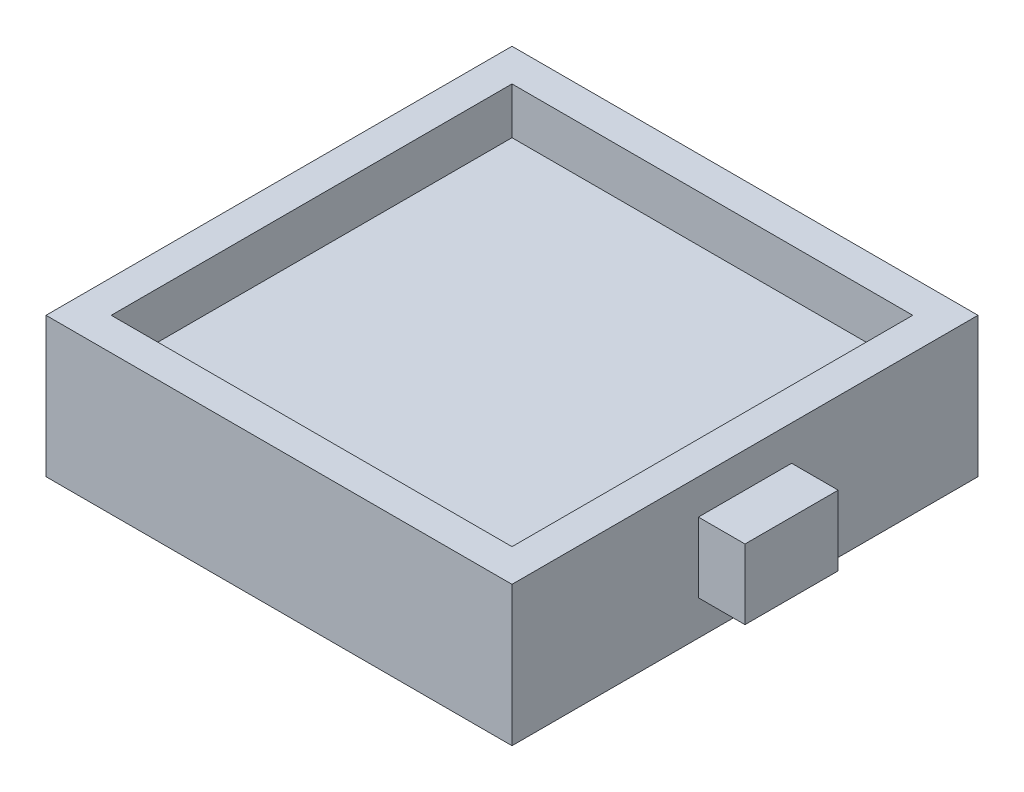
SolidWorks part; units mm, degrees
material "AISI 1020"
ref_plane "Front Plane" through (0, 0, 0) normal (0, 0, 1) x (1, 0, 0)
ref_plane "Top Plane" through (0, 0, 0) normal (0, 1, 0) x (1, 0, 0)
ref_plane "Right Plane" through (0, 0, 0) normal (1, 0, 0) x (0, 0, -1)
sketch "Sketch1" plane through (0, 0, 0) normal (0, 1, 0) x (1, 0, 0)
  line L1 (-50, 50) -> (50, 50)
  line L2 (-50, 50) -> (-50, -50)
  line L3 (-50, -50) -> (50, -50)
  line L4 (50, 50) -> (50, -50)
  line L5 (-50, 50) -> (50, -50) construction
  line L6 (-50, -50) -> (50, 50) construction
  point P0 (0, 0)
  dimension "D1" = 100
  dimension "D2" = 100
extrude "Boss-Extrude1" add sketch "Sketch1" against normal blind 30
sketch "Sketch2" plane through (0, 0, 0) normal (0, 1, 0) x (1, 0, 0)
  line L0 (50, 50) -> (-50, 50) construction
  line L1 (-43, -43) -> (43, -43)
  line L2 (-43, -43) -> (-43, 43)
  line L3 (-43, 43) -> (43, 43)
  line L4 (43, -43) -> (43, 43)
  line L5 (-43, -43) -> (43, 43) construction
  line L6 (-43, 43) -> (43, -43) construction
  line L7 (-50, 50) -> (-50, -50) construction
  point P0 (0, 0)
  dimension "D1" = 7
  dimension "D2" = 7
extrude "Cut-Extrude1" cut sketch "Sketch2" against normal blind 10
sketch "Sketch3" plane through (50, 0, 0) normal (1, 0, 0) x (0, 0, -1)
  line L0 (0, 0) -> (0, -15) construction
  line L1 (-10, -22.5) -> (10, -22.5)
  line L2 (-10, -22.5) -> (-10, -7.5)
  line L3 (-10, -7.5) -> (10, -7.5)
  line L4 (10, -22.5) -> (10, -7.5)
  line L5 (-10, -22.5) -> (10, -7.5) construction
  line L6 (-10, -7.5) -> (10, -22.5) construction
  point P0 (0, -15)
  dimension "D1" = 20
  dimension "D2" = 15
  dimension "D3" = 15
extrude "Boss-Extrude2" add sketch "Sketch3" along normal blind 10
